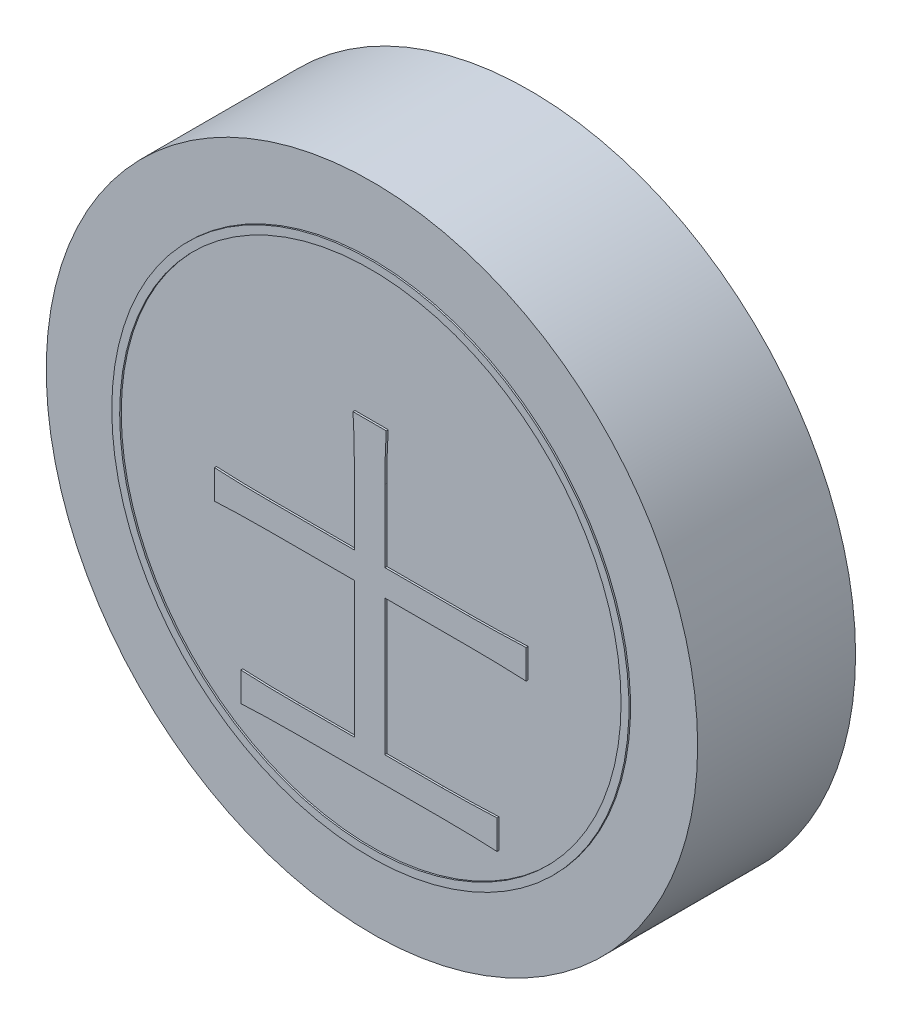
SolidWorks part; units mm, degrees
ref_plane "前视基准面" through (0, 0, 0) normal (0, 0, 1) x (1, 0, 0)
ref_plane "上视基准面" through (0, 0, 0) normal (0, 1, 0) x (1, 0, 0)
ref_plane "右视基准面" through (0, 0, 0) normal (1, 0, 0) x (0, 0, -1)
other "Configuration Table"
sketch "草图1" plane through (0, 0, 0) normal (0, 0, 1) x (1, 0, 0)
  circle A0 centre (0, 0) radius 16.5
  dimension "D1" = 33
extrude "Diameter33_Height8" add sketch "草图1" against normal blind 8
sketch "草图2" plane through (0, 0, 0) normal (0, 0, 1) x (1, 0, 0)
  text T0 "士" font "SimHei" height 12
extrude "Character_士" add sketch "草图2" along normal blind 0.1
sketch "草图3" plane through (0, 0, 0) normal (0, 0, 1) x (1, 0, 0)
  circle A0 centre (0, 0) radius 13.1
  circle A1 centre (0, 0) radius 12.7
extrude "Ink_ring" add sketch "草图3" along normal blind 0.08
